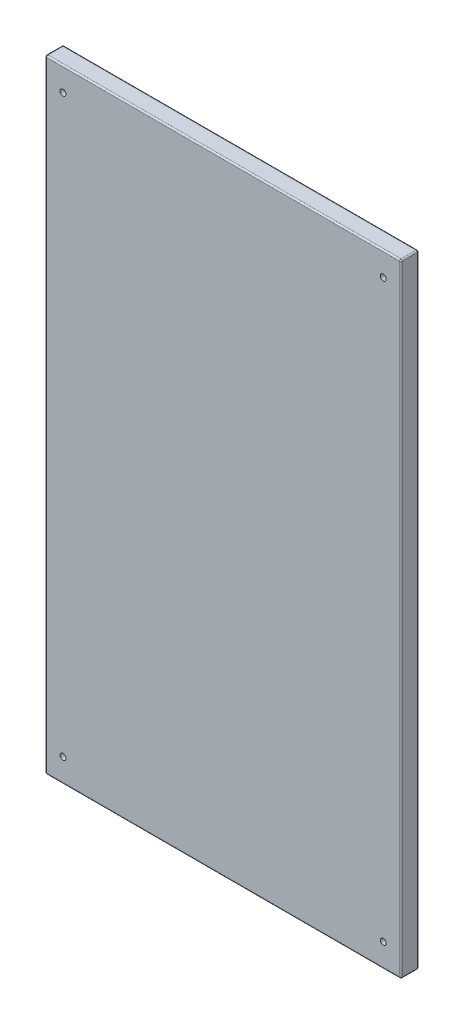
SolidWorks part; units mm, degrees
ref_plane "Front Plane" through (0, 0, 0) normal (0, 0, 1) x (1, 0, 0)
ref_plane "Top Plane" through (0, 0, 0) normal (0, 1, 0) x (1, 0, 0)
ref_plane "Right Plane" through (0, 0, 0) normal (1, 0, 0) x (0, 0, -1)
sketch "Sketch1" plane through (0, 0, 0) normal (0, 0, 1) x (1, 0, 0)
  line L1 (-120, 105) -> (0, 105)
  line L2 (-120, 105) -> (-120, -105)
  line L3 (-120, -105) -> (0, -105)
  line L4 (0, 105) -> (0, -105)
  point P4 (0, 0)
  dimension "D1" = 210
  dimension "D2" = 120
extrude "Boss-Extrude1" add sketch "Sketch1" along normal blind 6
sketch "Sketch2" plane through (0, 0, 0) normal (0, 0, -1) x (-1, 0, 0)
  line L0 (0, 105) -> (120, 105) construction
  line L1 (0, -105) -> (0, 105) construction
  line L2 (120, 105) -> (120, -105) construction
  line L3 (120, -105) -> (0, -105) construction
  circle A0 centre (6, 97) radius 2
  circle A1 centre (114, 97) radius 2
  circle A2 centre (6, -97) radius 2
  circle A3 centre (114, -97) radius 2
  dimension "D1" = 4
  dimension "D2" = 8
  dimension "D3" = 6
  dimension "D4" = 6
  dimension "D5" = 8
extrude "Cut-Extrude1" cut sketch "Sketch2" against normal blind 3
sketch "Sketch3" plane through (0, 0, 6) normal (0, 0, 1) x (1, 0, 0)
  line L0 (0, 105) -> (-120, 105) construction
  line L1 (-120, 105) -> (-120, -105) construction
  line L2 (0, -105) -> (0, 105) construction
  line L3 (-120, -105) -> (0, -105) construction
  circle A0 centre (-114, 97) radius 1
  circle A1 centre (-6, 97) radius 1
  circle A2 centre (-6, -97) radius 1
  circle A3 centre (-114, -97) radius 1
  point P14 (0, 0)
  point P15 (0, 0)
  point P16 (-5.9875, 105)
  dimension "D1" = 2
  dimension "D2" = 6
  dimension "8" = 8
  dimension "D3" = 6
  dimension "D4" = 8
extrude "Cut-Extrude2" cut sketch "Sketch3" against normal blind 3
fillet "Fillet1" radius 0.5 12 edges at (0, -105, 3) (-60, -105, 0) (-60, -105, 6) (-120, -105, 3) (-120, 0, 0) (-120, 0, 6) (-120, 105, 3) (-60, 105, 0) (-60, 105, 6) (0, 105, 3) (0, 0, 0) (0, 0, 6)
